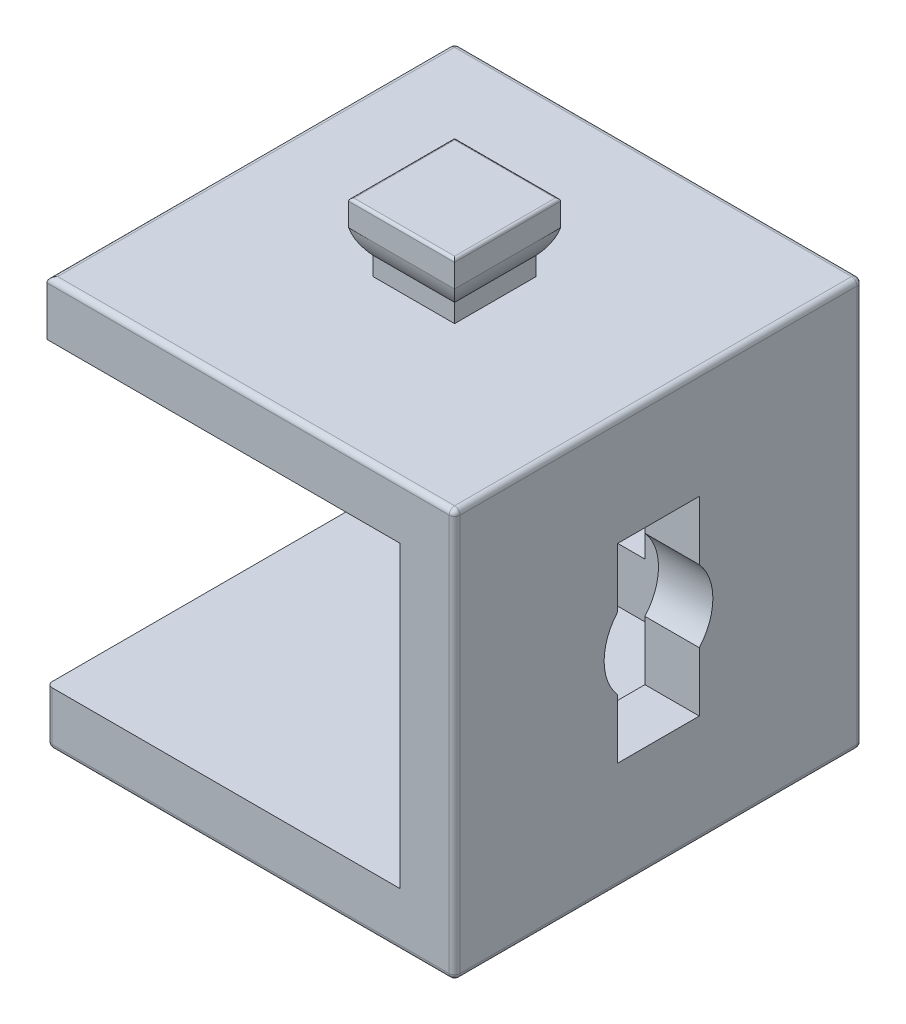
SolidWorks part; units mm, degrees
ref_plane "前视基准面" through (0, 0, 0) normal (0, 0, 1) x (1, 0, 0)
ref_plane "上视基准面" through (0, 0, 0) normal (0, 1, 0) x (1, 0, 0)
ref_plane "右视基准面" through (0, 0, 0) normal (1, 0, 0) x (0, 0, -1)
sketch "草图1" plane through (0, 0, 0) normal (0, 0, 1) x (1, 0, 0)
  line L1 (-7.5, 0) -> (7.5, 0)
  line L2 (-7.5, 0) -> (-7.5, 15)
  line L3 (-7.5, 15) -> (7.5, 15)
  line L4 (7.5, 0) -> (7.5, 15)
extrude "凸台-拉伸1" add sketch "草图1" against normal blind 15
sketch "草图2" plane through (-7.5, 0, 0) normal (-1, 0, 0) x (0, 0, 1)
  line L0 (0, 15) -> (0, 0) construction
  line L1 (-13, 2) -> (0, 2)
  line L2 (-13, 2) -> (-13, 13)
  line L3 (-13, 13) -> (0, 13)
  line L4 (0, 2) -> (0, 13)
  line L5 (-15, 15) -> (-15, 0) construction
  dimension "D1" = 2
  dimension "D2" = 2
  dimension "D3" = 2
extrude "切除-拉伸1" cut sketch "草图2" against normal blind 13
sketch "草图4" plane through (0, 0, 0) normal (0, 0, 1) x (1, 0, 0)
  line L2 (-1.5, 15.6771) -> (1.5, 15.6771)
  line L5 (-1.95, 17.5) -> (1.95, 17.5)
  line L6 (-1.95, 17.5) -> (-1.95, 16.5556)
  line L7 (1.95, 17.5) -> (1.95, 16.5556)
  arc A1 (-1.95, 16.5556) -> (-1.5, 15.6771) centre (0, 17) ccw
  arc A2 (1.5, 15.6771) -> (1.95, 16.5556) centre (0, 17) ccw
extrude "凸台-拉伸2" add sketch "草图4" against normal blind 6 from offset 4.5 offset against normal yes
sketch "草图5" plane through (0, 15, 0) normal (0, 1, 0) x (-1, 0, 0)
  line L1 (1.5, -9) -> (-1.5, -9)
  line L2 (1.5, -9) -> (1.5, -6)
  line L3 (1.5, -6) -> (-1.5, -6)
  line L4 (-1.5, -9) -> (-1.5, -6)
extrude "凸台-拉伸3" add sketch "草图5" along normal blind 1
sketch "草图6" plane through (0, 0, -15) normal (0, 0, -1) x (-1, 0, 0)
  line L0 (-1.5, 6.1771) -> (-1.5, 4)
  line L1 (-1.5, 11) -> (1.5, 11)
  line L2 (-1.5, 11) -> (-1.5, 8.8229)
  line L3 (-1.5, 4) -> (1.5, 4)
  line L4 (1.5, 11) -> (1.5, 8.8229)
  line L5 (1.5, 6.1771) -> (1.5, 4)
  arc A0 (-1.5, 8.8229) -> (-1.5, 6.1771) centre (0, 7.5) ccw
  arc A1 (1.5, 6.1771) -> (1.5, 8.8229) centre (0, 7.5) ccw
extrude "切除-拉伸3" cut sketch "草图6" against normal up to next
sketch "草图7" plane through (7.5, 0, 0) normal (1, 0, 0) x (0, 0, -1)
  line L0 (6, 6.1771) -> (6, 4)
  line L1 (6, 11) -> (9, 11)
  line L2 (6, 11) -> (6, 8.8229)
  line L3 (6, 4) -> (9, 4)
  line L4 (9, 11) -> (9, 8.8229)
  line L5 (9, 6.1771) -> (9, 4)
  arc A0 (6, 8.8229) -> (6, 6.1771) centre (7.5, 7.5) ccw
  arc A1 (9, 6.1771) -> (9, 8.8229) centre (7.5, 7.5) ccw
extrude "切除-拉伸4" cut sketch "草图7" against normal up to next
sketch "草图8" plane through (0, 0, 0) normal (1, 0, 0) x (0, 0, -1)
  line L2 (5.55, 17.5) -> (5.55, 16.5556)
  line L3 (7.5, 18.1799) -> (7.5, 15.0835) construction
  line L4 (6, 15.6771) -> (4.5, 15.6771)
  line L7 (6, 15.6771) -> (4.5, 15.6771) construction
  line L8 (4.5, 15.6771) -> (4.5, 17.5)
  line L9 (4.5, 17.5) -> (5.55, 17.5)
  line L10 (10.5, 17.5) -> (9.45, 17.5)
  line L11 (10.5, 15.6771) -> (10.5, 17.5)
  line L12 (9, 15.6771) -> (10.5, 15.6771)
  line L13 (9.45, 17.5) -> (9.45, 16.5556)
  arc A0 (5.55, 16.5556) -> (6, 15.6771) centre (7.5, 17) ccw
  arc A1 (9.45, 16.5556) -> (9, 15.6771) centre (7.5, 17) cw
extrude "切除-拉伸5" cut sketch "草图8" against normal up to next and the other way up to next
fillet "圆角1" radius 0.1 4 edges at (0, 17.5, -5.55) (-1.95, 17.5, -7.5) (0, 17.5, -9.45) (1.95, 17.5, -7.5)
fillet "圆角2" radius 0.2 12 edges at (0, 0, 0) (7.5, 0, -7.5) (0, 0, -15) (-7.5, 0, -7.5) (7.5, 7.5, -15) (0, 15, -15) (-7.5, 15, -7.5) (-7.5, 7.5, -15) (-7.5, 1, 0) (7.5, 7.5, 0) (7.5, 15, -7.5) (0, 15, 0)
sketch "草图9" plane through (0, 0, 0) normal (1, 0, 0) x (0, 0, -1)
  line L0 (7.5, 0) -> (7.5, -2) construction
  line L1 (14.8, 0) -> (0.2, 0) construction
  line L2 (7.5, -2) -> (7.5, -2.5) construction
  line L3 (6, 0) -> (9, 0)
  line L4 (9, 0) -> (9, -0.6771)
  line L5 (5.55, -2.5) -> (9.45, -2.5)
  line L6 (9.45, -2.5) -> (9.45, -1.5556)
  line L7 (5.55, -2.5) -> (5.55, -1.5556)
  line L8 (6, 0) -> (6, -0.6771)
  arc A0 (9.45, -1.5556) -> (9, -0.6771) centre (7.5, -2) ccw
  arc A1 (5.55, -1.5556) -> (6, -0.6771) centre (7.5, -2) cw
  dimension "D5" = 2
  dimension "D1" = 2
  dimension "D2" = 0.5
  dimension "D3" = 1.5
  dimension "D4" = 1.95
extrude "凸台-拉伸4" add sketch "草图9" along normal blind 3 and the other way blind 3
sketch "草图10" plane through (0, 0, 0) normal (0, 0, 1) x (1, 0, 0)
  line L0 (0, 0) -> (0, -2) construction
  line L1 (0, -2) -> (0, -2.5) construction
  line L2 (-3, -2.5) -> (3, -2.5) construction
  line L4 (-1.95, -2.5) -> (-1.95, -1.5556)
  line L5 (-3, 0) -> (3, 0) construction
  line L6 (1.5, 0) -> (1.5, -0.6771)
  line L7 (-1.5, 0) -> (-1.5, -0.6771)
  line L8 (1.95, -2.5) -> (1.95, -1.5556)
  line L9 (1.95, -2.5) -> (3, -2.5)
  line L10 (-3, 0) -> (-1.5, 0)
  line L11 (-3, 0) -> (-3, -2.5)
  line L12 (-3, -2.5) -> (-1.95, -2.5)
  line L13 (3, 0) -> (3, -2.5)
  line L14 (1.5, 0) -> (3, 0)
  arc A0 (1.95, -1.5556) -> (1.5, -0.6771) centre (0, -2) ccw
  arc A1 (-1.95, -1.5556) -> (-1.5, -0.6771) centre (0, -2) cw
  dimension "D1" = 2
  dimension "D2" = 1.5
  dimension "D3" = 1.95
extrude "切除-拉伸6" cut sketch "草图10" against normal blind 15
fillet "圆角3" radius 0.1 4 edges at (1.95, -2.5, -7.5) (0, -2.5, -9.45) (-1.95, -2.5, -7.5) (0, -2.5, -5.55)
